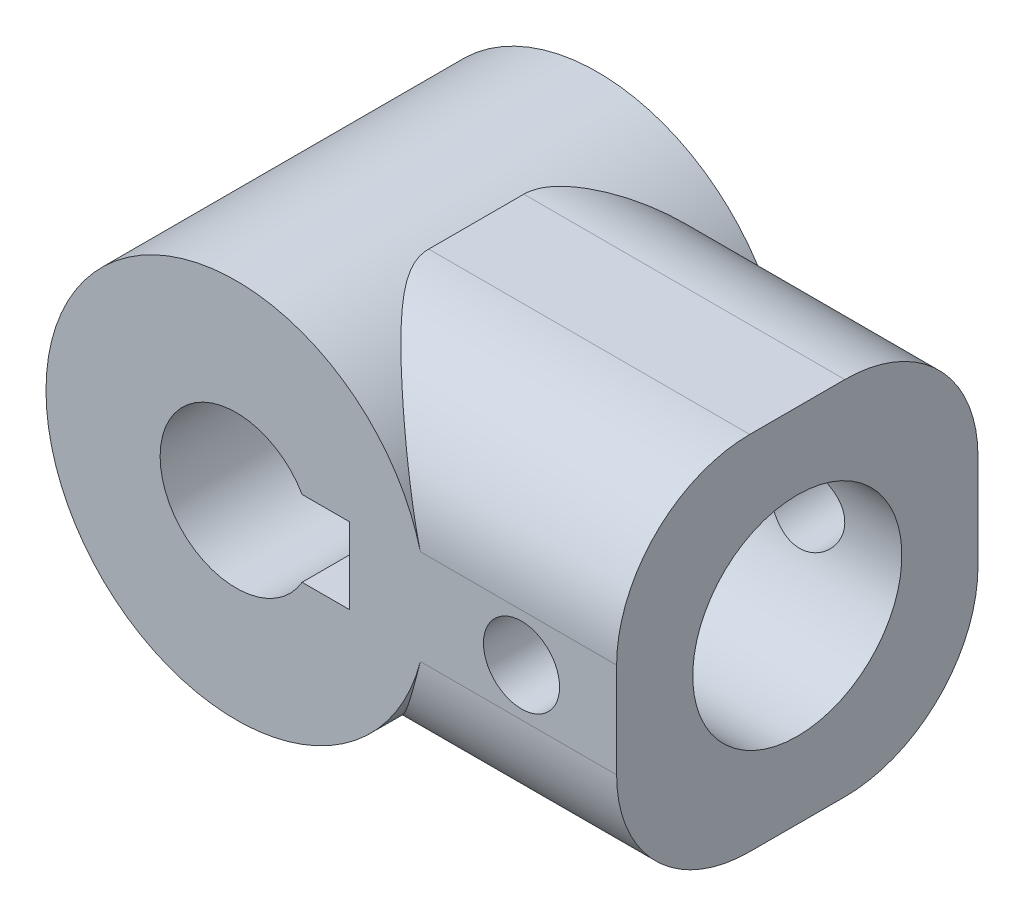
SolidWorks part; units mm, degrees
ref_plane "Plano frontal" through (0, 0, 0) normal (0, 0, 1) x (1, 0, 0)
ref_plane "Plano superior" through (0, 0, 0) normal (0, 1, 0) x (1, 0, 0)
ref_plane "Plano direito" through (0, 0, 0) normal (1, 0, 0) x (0, 0, -1)
sketch "Esboço1" plane through (0, 0, 0) normal (0, 0, 1) x (1, 0, 0)
  line L4 (5, 0) -> (5, 9.5)
  line L5 (5, 0) -> (5, -9.5)
  line L6 (5, -9.5) -> (-11.8775, -9.5)
  line L7 (5, 9.5) -> (-11.8775, 9.5)
  arc A0 (-11.8775, 9.5) -> (-11.8775, -9.5) centre (-15, 0) ccw
  circle A1 centre (-15, 0) radius 4
  circle A2 centre (0, 0) radius 2
  circle A3 centre (-15, 0) radius 4
  arc A4 (-11.8775, 9.5) -> (-11.8775, -9.5) centre (-15, 0) ccw
extrude "Ressalto-extrusão1" add sketch "Esboço1" along normal blind 19
fillet "Filete1" radius 7 4 edges at (-3.4388, -9.5, 0) (-3.4388, -9.5, 19) (-3.4388, 9.5, 0) (-3.4388, 9.5, 19)
sketch "Esboço3" plane through (5, 0, 0) normal (1, 0, 0) x (0, 0, -1)
  line L0 (-12, -9.5) -> (-7, -9.5) construction
  circle A1 centre (-9.5, 0) radius 5.4973
  dimension "D1" = 10.9947
  dimension "D2" = 9.5
  dimension "D3" = 9.5
extrude "Corte-extrusão1" cut sketch "Esboço3" against normal blind 12.5
sketch "Esboço5" plane through (0, 0, 0) normal (0, 0, -1) x (-1, 0, 0)
  line L0 (-5, 2.5) -> (-5, -2.5) construction
  line L5 (15, 4) -> (15, -4) construction
  line L6 (9.0359, -2) -> (11.5359, -2)
  line L7 (9.0359, 0) -> (9.0359, -2)
  line L8 (9.0359, 2) -> (11.5359, 2)
  line L9 (9.0359, 0) -> (9.0359, 2)
  line L10 (11.5359, 2) -> (9.0359, 2)
  arc A2 (11.5359, -2) -> (11.5359, 2) centre (15, 0) cw
  circle M8 centre (15, 0) radius 4
  dimension "D1" = 4
  dimension "D2" = 14.0359
  dimension "D3" = 14.0359
  dimension "D4" = 16.5359
  dimension "D5" = 16.5359
  dimension "D6" = 20
  dimension "D7" = 0.5
  dimension "D9" = 2.5
  dimension "D11" = 4.5
extrude "Corte-extrusão5" cut sketch "Esboço5" against normal through all contours L9 L7 L6 L8 M8
